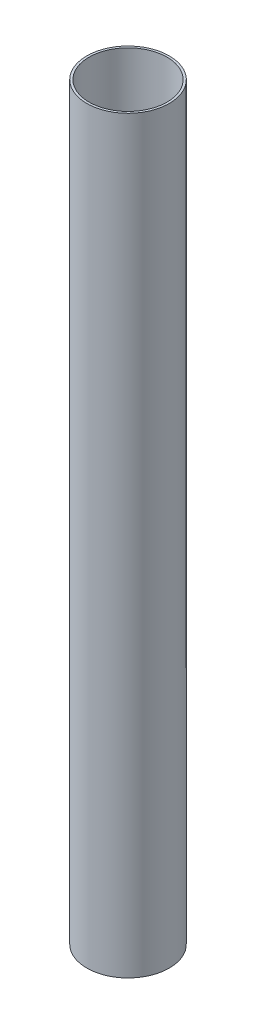
SolidWorks part; units mm, degrees
ref_plane "Front Plane" through (0, 0, 0) normal (0, 0, 1) x (1, 0, 0)
ref_plane "Top Plane" through (0, 0, 0) normal (0, 1, 0) x (1, 0, 0)
ref_plane "Right Plane" through (0, 0, 0) normal (1, 0, 0) x (0, 0, -1)
sketch "Sketch2" plane through (0, 0, 0) normal (0, 1, 0) x (1, 0, 0)
  circle A0 centre (0, 0) radius 33.57
  circle A1 centre (0, 0) radius 31.75
  dimension "D1" = 63.5
  dimension "D2" = 1.82
extrude "Boss-Extrude1" add sketch "Sketch2" along normal blind 609.6
